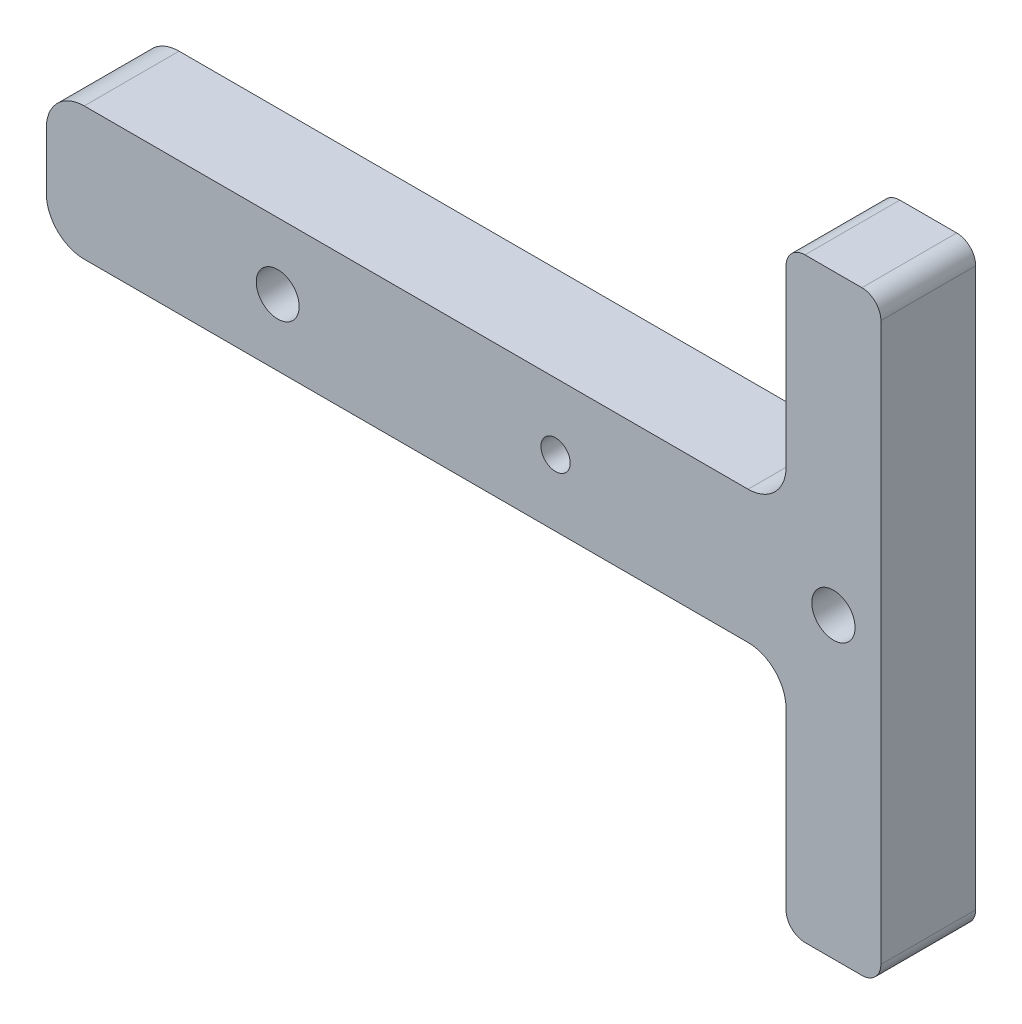
SolidWorks part; units mm, degrees
ref_plane "Front Plane" through (0, 0, 0) normal (0, 0, 1) x (1, 0, 0)
ref_plane "Top Plane" through (0, 0, 0) normal (0, 1, 0) x (1, 0, 0)
ref_plane "Right Plane" through (0, 0, 0) normal (1, 0, 0) x (0, 0, -1)
sketch "Sketch1" plane through (0, 0, 0) normal (0, 0, 1) x (1, 0, 0)
  line L0 (-17.5, 0) -> (17.5, 0)
  line L1 (-17.5, -7) -> (17.5, -7)
  line L2 (-19.5, -2) -> (-19.5, -5)
  line L3 (19.5, 2) -> (19.5, 11.2)
  line L4 (20.5, 12.2) -> (23.5, 12.2)
  line L5 (24.5, 11.2) -> (24.5, -18.2)
  line L6 (-19.5, -3.5) -> (37.202, -3.5) construction
  line L7 (19.5, -9) -> (19.5, -18.2)
  line L8 (20.5, -19.2) -> (23.5, -19.2)
  line L9 (-19.5, 0) -> (19.5, 0) construction
  line L10 (-19.5, -7) -> (19.5, -7) construction
  arc A0 (17.5, 0) -> (19.5, 2) centre (17.5, 2) ccw
  arc A1 (17.5, -7) -> (19.5, -9) centre (17.5, -9) cw
  arc A2 (-17.5, -7) -> (-19.5, -5) centre (-17.5, -5) cw
  arc A3 (-17.5, 0) -> (-19.5, -2) centre (-17.5, -2) ccw
  arc A4 (19.5, -18.2) -> (20.5, -19.2) centre (20.5, -18.2) ccw
  arc A5 (23.5, -19.2) -> (24.5, -18.2) centre (23.5, -18.2) ccw
  arc A6 (23.5, 12.2) -> (24.5, 11.2) centre (23.5, 11.2) cw
  arc A7 (19.5, 11.2) -> (20.5, 12.2) centre (20.5, 11.2) cw
  point P4 (0, 0)
  point P14 (24.5, -3.5)
  point P17 (19.5, 0)
  point P21 (19.5, -7)
  point P30 (19.5, -19.2)
  point P33 (24.5, -19.2)
  point P36 (24.5, 12.2)
  point P39 (19.5, 12.2)
  dimension "D5" = 2
  dimension "D1" = 1
  dimension "D3" = 5
  dimension "D4" = 12.2
  dimension "D2" = 7
extrude "Boss-Extrude1" add sketch "Sketch1" along normal blind 5
sketch "Sketch2" plane through (0, 0, 5) normal (0, 0, 1) x (1, 0, 0)
  line L0 (22, 12.2) -> (22, -21.4503) construction
  line L1 (23.5, 12.2) -> (20.5, 12.2) construction
  line L2 (-19.5, -3.5) -> (29.3804, -3.5) construction
  line L3 (-19.5, -2) -> (-19.5, -5) construction
  circle A0 centre (22, -3.5) radius 1.141
  circle A1 centre (-7.3, -3.5) radius 1.1302
  point P12 (0, 0)
  point P13 (0, 0)
  dimension "D1" = 29.3
extrude "Cut-Extrude1" cut sketch "Sketch2" against normal through all
sketch "Sketch3" plane through (0, 0, 5) normal (0, 0, 1) x (1, 0, 0)
  line L0 (-7.3, -3.5) -> (31.8159, -3.5) construction
  line L1 (22, -3.5) -> (22, -14.189) construction
  circle A0 centre (7.35, -3.5) radius 0.77
  dimension "D1" = 1.54
  dimension "D2" = 14.65
extrude "Cut-Extrude2" cut sketch "Sketch3" against normal blind 3
cosmetic thread "Cosmetic Thread1" parameters "D2"=2
